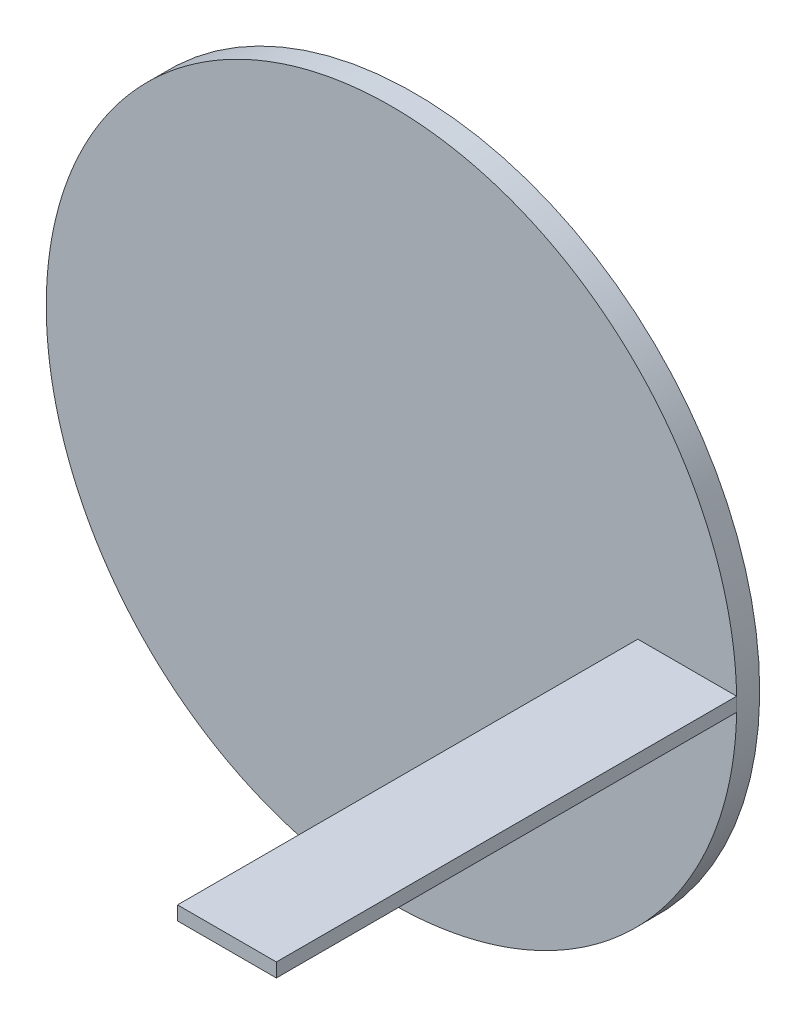
SolidWorks part; units mm, degrees
ref_plane "Plano frontal" through (0, 0, 0) normal (1, 0, 0) x (0, 1, 0)
ref_plane "Plano superior" through (0, 0, 0) normal (0, 0, 1) x (0, 1, 0)
ref_plane "Plano direito" through (0, 0, 0) normal (0, 1, 0) x (-1, 0, 0)
sketch "Esboço1" plane through (0, 0, 0) normal (0, 0, 1) x (0, 1, 0)
  circle A0 centre (0, 0) radius 75
extrude "Ressalto-extrusão1" add sketch "Esboço1" along normal blind 5
sketch "Esboço2" plane through (0, 0, 5) normal (0, 0, 1) x (1, 0, 0)
  circle A0 centre (0, 0) radius 10
extrude "Ressalto-extrusão2" add sketch "Esboço2" against normal blind 30
sketch "Esboço4" plane through (0, 0, 5) normal (0, 0, 1) x (1, 0, 0)
  line L1 (74.9846, -1.5182) -> (53.5162, -1.5182)
  line L2 (74.9846, -1.5182) -> (74.9846, 1.505)
  line L3 (74.9846, 1.505) -> (53.5162, 1.505)
  line L4 (53.5162, -1.5182) -> (53.5162, 1.505)
  circle A0 centre (0, 0) radius 75 construction
extrude "Ressalto-extrusão3" add sketch "Esboço4" along normal blind 100
